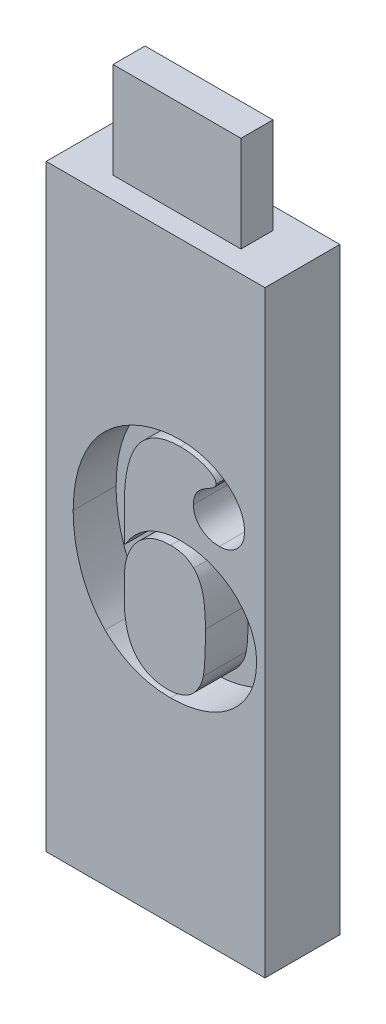
SolidWorks part; units mm, degrees
ref_plane "Front Plane" through (0, 0, 0) normal (0, 0, 1) x (1, 0, 0)
ref_plane "Top Plane" through (0, 0, 0) normal (0, 1, 0) x (1, 0, 0)
ref_plane "Right Plane" through (0, 0, 0) normal (1, 0, 0) x (0, 0, -1)
sketch "Sketch1" plane through (0, 0, 0) normal (0, 0, 1) x (1, 0, 0)
  line L1 (-8.69, -23.749) -> (8.69, -23.749)
  line L2 (-8.69, -23.749) -> (-8.69, 23.749)
  line L3 (-8.69, 23.749) -> (8.69, 23.749)
  line L4 (8.69, -23.749) -> (8.69, 23.749)
  line L5 (-8.69, -23.749) -> (8.69, 23.749) construction
  line L6 (-8.69, 23.749) -> (8.69, -23.749) construction
  point P0 (0, 0)
  dimension "D1" = 17.38
  dimension "D2" = 47.498
extrude "Boss-Extrude1" add sketch "Sketch1" along normal blind 5.95
sketch "Sketch2" plane through (0, 0, 5.95) normal (0, 0, 1) x (1, 0, 0)
  line L0 (0, 23.749) -> (0, -23.749) construction
  line L1 (8.69, 23.749) -> (-8.69, 23.749) construction
  line L2 (-8.69, -23.749) -> (8.69, -23.749) construction
  line L3 (0, -23.749) -> (0, 0) construction
  line L4 (0, 0) -> (-8.69, 0) construction
  line L5 (-8.69, 23.749) -> (-8.69, -23.749) construction
  line L6 (-8.69, 0) -> (8.69, 0) construction
  line L7 (8.69, -23.749) -> (8.69, 23.749) construction
  line L8 (-8.69, -23.749) -> (8.69, -23.749) construction
  line L9 (-8.69, -21.209) -> (8.69, -21.209) construction
  line L10 (-8.69, -18.669) -> (8.69, -18.669) construction
  line L11 (-8.69, -16.129) -> (8.69, -16.129) construction
  line L12 (-8.69, -13.589) -> (8.69, -13.589) construction
  line L13 (-8.69, -11.049) -> (8.69, -11.049) construction
  line L14 (-8.69, -8.509) -> (8.69, -8.509) construction
  line L15 (-8.69, -5.969) -> (8.69, -5.969) construction
  line L16 (-8.69, -3.429) -> (8.69, -3.429) construction
  line L17 (-8.69, -0.889) -> (8.69, -0.889) construction
  line L18 (-8.69, 1.651) -> (8.69, 1.651) construction
  line L19 (-8.69, 4.191) -> (8.69, 4.191) construction
  line L20 (-8.69, 6.731) -> (8.69, 6.731) construction
  line L21 (-8.69, 9.271) -> (8.69, 9.271) construction
  line L22 (-8.69, 11.811) -> (8.69, 11.811) construction
  line L23 (-8.69, 14.351) -> (8.69, 14.351) construction
  line L24 (-8.69, 16.891) -> (8.69, 16.891) construction
  line L25 (-8.69, 19.431) -> (8.69, 19.431) construction
  line L26 (-8.69, 21.971) -> (8.69, 21.971) construction
  line L27 (-8.69, 23.749) -> (-8.69, -23.749) construction
  line L28 (-6.15, 23.749) -> (-6.15, -23.749) construction
  line L29 (-3.61, 23.749) -> (-3.61, -23.749) construction
  line L30 (-1.07, 23.749) -> (-1.07, -23.749) construction
  line L31 (1.47, 23.749) -> (1.47, -23.749) construction
  line L32 (4.01, 23.749) -> (4.01, -23.749) construction
  line L33 (6.55, 23.749) -> (6.55, -23.749) construction
  text T0 "6\r\n" font "Engravers MT" height in points 72
  dimension "D1" = 19
  dimension "D2" = 2.54
  dimension "D4" = 2.54
  dimension "D3" = 7
extrude "Cut-Extrude1" cut sketch "Sketch2" against normal blind 3.41
sketch "Sketch3" plane through (0, 23.749, 0) normal (0, 1, 0) x (1, 0, 0)
  line L0 (0, 0) -> (0, -5.95) construction
  line L1 (8.69, -5.95) -> (-8.69, -5.95) construction
  line L2 (0, -5.95) -> (0, -2.975) construction
  line L3 (0, -2.975) -> (-8.69, -2.975) construction
  line L4 (-8.69, -5.95) -> (-8.69, 0) construction
  line L5 (-8.69, -2.975) -> (8.69, -2.975) construction
  line L6 (8.69, -5.95) -> (8.69, 0) construction
  line L8 (-5.08, -4.245) -> (5.08, -4.245)
  line L9 (-5.08, -4.245) -> (-5.08, -1.705)
  line L10 (-5.08, -1.705) -> (5.08, -1.705)
  line L11 (5.08, -4.245) -> (5.08, -1.705)
  line L12 (-5.08, -4.245) -> (5.08, -1.705) construction
  line L13 (-5.08, -1.705) -> (5.08, -4.245) construction
  dimension "D1" = 2.54
  dimension "D2" = 10.16
extrude "Boss-Extrude2" add sketch "Sketch3" along normal blind 7.62
